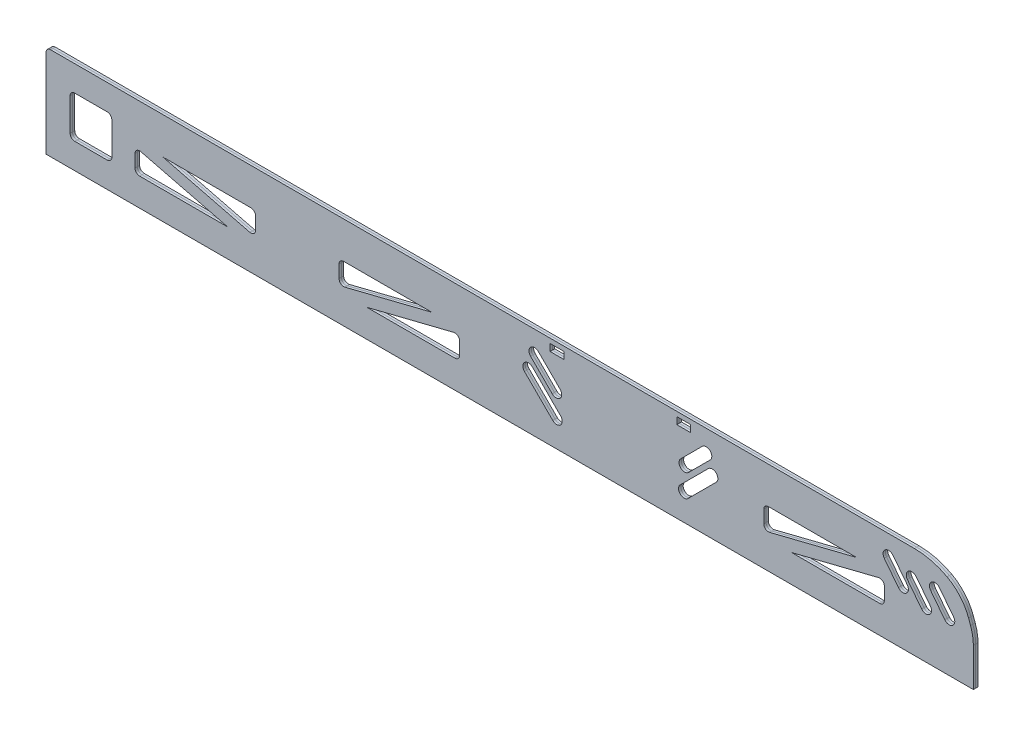
SolidWorks part; units mm, degrees
ref_plane "Front Plane" through (0, 0, 0) normal (0, 0, 1) x (1, 0, 0)
ref_plane "Top Plane" through (0, 0, 0) normal (0, 1, 0) x (1, 0, 0)
ref_plane "Right Plane" through (0, 0, 0) normal (1, 0, 0) x (0, 0, -1)
sketch "Sketch1" plane through (0, 0, 0) normal (0, 0, 1) x (1, 0, 0)
  line L0 (-200, 10) -> (-200, 20)
  line L1 (0, 0) -> (-200, 0) construction
  line L2 (0, 0) -> (0, 20) construction
  line L3 (0, 20) -> (-200, 20) construction
  line L4 (-200, 10) -> (-200, 20)
  line L5 (-100, 20) -> (-100, 0) construction
  line L6 (0, 10) -> (-200, 10) construction
  line L7 (-190, 0) -> (0, 0) construction
  line L8 (60.7449, 36.303) -> (260.1814, 21.3) construction
  line L9 (-180.8, 11) -> (-180.8, 6)
  line L10 (-194.8, 14.5) -> (-185.8, 14.5)
  line L11 (-194.8, 14.5) -> (-194.8, 5.5)
  line L12 (-194.8, 5.5) -> (-185.8, 5.5)
  line L13 (-185.8, 14.5) -> (-185.8, 5.5)
  line L14 (-190.3, 5.5) -> (-190.3, 14.5) construction
  line L15 (-194.8, 10) -> (-185.8, 10) construction
  line L16 (-180.8, 6) -> (-160.8, 6)
  line L17 (-160.8, 6) -> (-180.8, 11)
  line L18 (-175.1796, 10.8834) -> (-154.8, 5.7885) construction
  line L19 (-154.8, 7.0769) -> (-154.8, 12.0769)
  line L20 (-154.8, 12.0769) -> (-174.8, 12.0769)
  line L21 (-174.8, 12.0769) -> (-154.8, 7.0769)
  line L22 (-145.8, 16.5491) -> (-145.8, 2.1149) construction
  line L23 (-130.8, 6) -> (-110.8, 11)
  line L24 (-110.8, 6) -> (-130.8, 6)
  line L25 (-110.8, 11) -> (-110.8, 6)
  line L26 (-136.8, 7.0769) -> (-136.8, 12.0769)
  line L27 (-116.8, 12.0769) -> (-136.8, 7.0769)
  line L28 (-136.8, 12.0769) -> (-116.8, 12.0769)
  line L29 (-95.9515, 11.8485) -> (-89.8704, 5.7674) construction
  line L30 (-95.1029, 12.6971) -> (-89.0218, 6.6159)
  line L31 (-96.8, 11) -> (-90.7189, 4.9189)
  line L32 (-94.6431, 15.3485) -> (-89.9762, 10.6816) construction
  line L33 (-93.7946, 16.1971) -> (-89.1277, 11.5302)
  line L34 (-95.4917, 14.5) -> (-90.8248, 9.8331)
  line L35 (-76.1277, 16.7406) -> (-76.1277, 1.5062) construction
  line L36 (-60.9608, 18.25) -> (-63.9608, 18.25) construction
  line L37 (-91.2946, 19) -> (-88.2946, 19)
  line L38 (-91.2946, 19) -> (-91.2946, 17.5)
  line L39 (-91.2946, 17.5) -> (-88.2946, 17.5)
  line L40 (-88.2946, 19) -> (-88.2946, 17.5)
  line L41 (-89.7946, 17.5) -> (-89.7946, 19) construction
  line L42 (-91.2946, 18.25) -> (-88.2946, 18.25) construction
  line L43 (-62.4608, 17.5) -> (-62.4608, 19) construction
  line L44 (-63.9608, 19) -> (-63.9608, 17.5)
  line L45 (-60.9608, 17.5) -> (-63.9608, 17.5)
  line L46 (-60.9608, 19) -> (-60.9608, 17.5)
  line L47 (-60.9608, 19) -> (-63.9608, 19)
  line L48 (-57.6123, 15.3485) -> (-62.2792, 10.6816) construction
  line L49 (-58.4608, 16.1971) -> (-63.1277, 11.5302)
  line L50 (-56.7638, 14.5) -> (-61.4307, 9.8331)
  line L51 (-56.304, 11.8485) -> (-62.3851, 5.7674) construction
  line L52 (-57.1525, 12.6971) -> (-63.2336, 6.6159)
  line L53 (-55.4554, 11) -> (-61.5365, 4.9189)
  line L54 (-24.8204, 10.8834) -> (-45.2, 5.7885) construction
  line L55 (-25.2, 12.0769) -> (-45.2, 7.0769)
  line L56 (-45.2, 12.0769) -> (-25.2, 12.0769)
  line L57 (-45.2, 7.0769) -> (-45.2, 12.0769)
  line L58 (-39.2, 6) -> (-19.2, 11)
  line L59 (-19.2, 6) -> (-39.2, 6)
  line L60 (-19.2, 11) -> (-19.2, 6)
  line L61 (-200, 10) -> (-200, 0)
  line L62 (-200, 0) -> (-190, 0)
  line L63 (-10, 0) -> (-200, 0)
  line L64 (0, 20) -> (0, 10) construction
  line L65 (-10, 0) -> (0, 0)
  line L66 (0, 0) -> (0, 10)
  line L67 (-12.6863, 20) -> (-200, 20)
  line L68 (0, 10) -> (0, 0)
  line L69 (0, 10) -> (-1.9431, 15.3485)
  line L70 (-18.2706, 15.6552) -> (-15.2087, 11.7024) construction
  line L71 (-17.322, 16.3901) -> (-14.26, 12.4373)
  line L72 (-19.2193, 14.9203) -> (-16.1574, 10.9675)
  line L73 (-13.2706, 14.1721) -> (-10.2087, 10.2194) construction
  line L74 (-12.322, 14.907) -> (-9.26, 10.9542)
  line L75 (-14.2193, 13.4373) -> (-11.1574, 9.4845)
  line L76 (-8.2706, 14.6419) -> (-5.2087, 10.6891) construction
  line L77 (-7.322, 15.3767) -> (-4.26, 11.424)
  line L78 (-9.2193, 13.907) -> (-6.1574, 9.9542)
  arc A0 (-1.9431, 15.3485) -> (-12.6863, 20) centre (-12.6863, 5.2678) ccw
  arc A1 (-95.1029, 12.6971) -> (-96.8, 11) centre (-95.9515, 11.8485) ccw
  arc A2 (-90.7189, 4.9189) -> (-89.0218, 6.6159) centre (-89.8704, 5.7674) ccw
  arc A3 (-93.7946, 16.1971) -> (-95.4917, 14.5) centre (-94.6431, 15.3485) ccw
  arc A4 (-90.8248, 9.8331) -> (-89.1277, 11.5302) centre (-89.9762, 10.6816) ccw
  arc A5 (-58.4608, 16.1971) -> (-56.7638, 14.5) centre (-57.6123, 15.3485) cw
  arc A6 (-61.4307, 9.8331) -> (-63.1277, 11.5302) centre (-62.2792, 10.6816) cw
  arc A7 (-57.1525, 12.6971) -> (-55.4554, 11) centre (-56.304, 11.8485) cw
  arc A8 (-61.5365, 4.9189) -> (-63.2336, 6.6159) centre (-62.3851, 5.7674) cw
  arc A9 (-17.322, 16.3901) -> (-19.2193, 14.9203) centre (-18.2706, 15.6552) ccw
  arc A10 (-16.1574, 10.9675) -> (-14.26, 12.4373) centre (-15.2087, 11.7024) ccw
  arc A11 (-12.322, 14.907) -> (-14.2193, 13.4373) centre (-13.2706, 14.1721) ccw
  arc A12 (-11.1574, 9.4845) -> (-9.26, 10.9542) centre (-10.2087, 10.2194) ccw
  arc A13 (-7.322, 15.3767) -> (-9.2193, 13.907) centre (-8.2706, 14.6419) ccw
  arc A14 (-6.1574, 9.9542) -> (-4.26, 11.424) centre (-5.2087, 10.6891) ccw
  point P30 (-92.9109, 8.808)
  point P35 (-92.3097, 13.0151)
  point P45 (-89.1277, 9.8331)
  point P58 (-62.4608, 18.25)
  point P61 (-59.9457, 13.0151)
  point P68 (-59.3445, 8.808)
  point P86 (-16.7397, 13.6788)
  point P91 (-11.7397, 12.1958)
  point P98 (-6.7397, 12.6655)
  point P104 (-89.7946, 18.25)
  point P156 (-100, 10)
  point P158 (-190.3, 10)
  dimension "D3" = 200
  dimension "D12" = 11
  dimension "D13" = 9
  dimension "D14" = 1.2
  dimension "D27" = 1
  dimension "D28" = 1.2
  dimension "D1" = 200
  dimension "D2" = 20
  dimension "D4" = 9
  dimension "D5" = 5.2
  dimension "D6" = 9
  dimension "D7" = 20
  dimension "D8" = 5
  dimension "D9" = 5
  dimension "D10" = 1.25
  dimension "D11" = 9
  dimension "D15" = 14
  dimension "D16" = 45
  dimension "D17" = 1
  dimension "D18" = 13
  dimension "D19" = 3.5
  dimension "D20" = 3
  dimension "D21" = 1.5
  dimension "D22" = 1
  dimension "D23" = 2.5
  dimension "D24" = 6
  dimension "D25" = 70.034
  dimension "D26" = 1
  dimension "D29" = 5
  dimension "D30" = 5
  dimension "D31" = 5
extrude "Boss-Extrude1" add sketch "Sketch1" along normal mid plane 1 contours L69 A0 L67 L0 L61 L62 L63 L65 L66 A14 L78 A13 L77 A12 L75 A11 L74 A10 L72 A9 L71 A4 L34 A3 L33 A2 L31 A1 L30 L58 L60 L59 L55 L57 L56 L37 L40 L39 L38 L26 L28 L27
fillet "Fillet1" radius 10 2 edges at (-1.9431, 15.3485, 0) (0, 10, 0)
fillet "Fillet3" radius 1 17 edges at (-185.8, 5.5, 0) (-185.8, 14.5, 0) (-194.8, 14.5, 0) (-194.8, 5.5, 0) (-19.2, 11, 0) (-19.2, 6, 0) (-45.2, 7.0769, 0) (-45.2, 12.0769, 0) (-110.8, 11, 0) (-110.8, 6, 0) (-136.8, 12.0769, 0) (-136.8, 7.0769, 0) (-154.8, 12.0769, 0) (-154.8, 7.0769, 0) (-180.8, 11, 0) (-180.8, 6, 0) (-200, 20, 0)
ref_plane "Plane2" through (0, 0, 0) normal (0, 0, 1) x (1, 0, 0)
split "Split1" trim tools "Plane2" bodies to split 101 resulting bodies 104 105
split "Split2" trim tools "Plane2" bodies to split 105 104 resulting bodies 106 107
